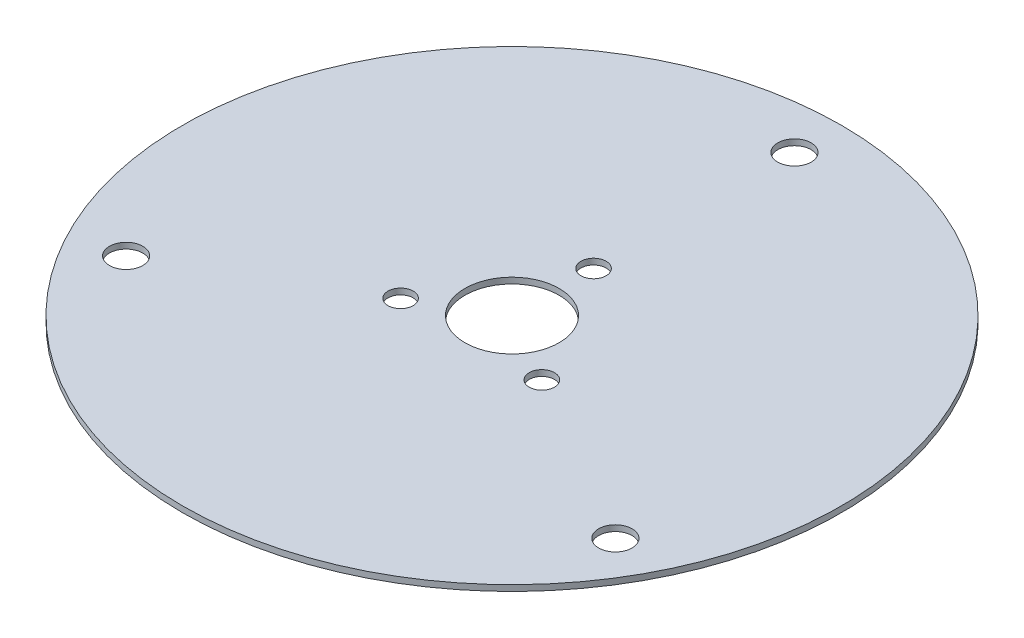
SolidWorks part; units mm, degrees
ref_plane "Front Plane" through (0, 0, 0) normal (0, 0, 1) x (1, 0, 0)
ref_plane "Top Plane" through (0, 0, 0) normal (0, 1, 0) x (1, 0, 0)
ref_plane "Right Plane" through (0, 0, 0) normal (1, 0, 0) x (0, 0, -1)
sketch "Sketch1" plane through (0, 0, 0) normal (0, 1, 0) x (1, 0, 0)
  circle A1 centre (0, 0) radius 44.45
  dimension "D2" = 88.9
extrude "Boss-Extrude1" add sketch "Sketch1" along normal blind 0.8
sketch "Sketch2" plane through (0, 0, 0) normal (0, 0, 1) x (1, 0, 0)
  line L0 (0, 6.2846) -> (0, -3.885) construction
sketch "Sketch7" plane through (0, 0.8, 0) normal (0, 1, 0) x (1, 0, 0)
  line L0 (0, 0) -> (0, 38.1) construction
  line L1 (0, 0) -> (32.9956, -19.05) construction
  line L2 (0, 0) -> (-32.9956, -19.05) construction
  point P10 (0, 0)
  dimension "D2" = 38.1
  dimension "D3" = 3
hole_wizard "M4 Clearance Hole1" positions "Sketch9" profile "Sketch8" hole size "M4" standard "ANSI Metric" end condition through all
sketch "Sketch9" plane through (0, 0.8, 0) normal (0, 1, 0) x (1, 0, 0)
  point P0 (0, 38.1)
  point P3 (-32.9956, -19.05)
  point P6 (32.9956, -19.05)
sketch "Sketch8" plane through (0, 0.8, -38.1) normal (1, 0, 0) x (0, 0, 1)
  line L0 (0, 0) -> (0, 0.8)
  line L1 (0, 0.8) -> (2.25, 0.8)
  line L2 (2.25, 0.8) -> (2.25, 0)
  line L5 (2.25, 0) -> (0, 0)
  line L11 (0, -6.35) -> (0, 107.95) construction
  dimension "Thru Hole Dia." = 4.5
  dimension "Thru Hole Depth" = 0.8
sketch "Sketch10" plane through (0, 0.8, 0) normal (0, 1, 0) x (1, 0, 0)
  line L0 (0, 0) -> (-38.4948, 22.225) construction
  line L1 (0, 0) -> (0, -44.45) construction
  line L2 (0, 0) -> (38.4948, 22.225) construction
  circle A0 centre (0, 0) radius 44.45 construction
  dimension "D1" = 120
  dimension "D2" = 120
sketch "Sketch11" plane through (0, 0.8, 0) normal (0, 1, 0) x (1, 0, 0)
  circle A6 centre (0, 0) radius 6.35
  dimension "D4" = 12.7
extrude "Cut-Extrude1" cut sketch "Sketch11" against normal through all
sketch "Sketch12" plane through (0, 0.8, 0) normal (0, 1, 0) x (1, 0, 0)
  line L0 (-9.5263, -5.5) -> (0, 0) construction
  line L1 (0, 0) -> (0, 11) construction
  line L2 (0, 11) -> (9.5263, -5.5) construction
  line L3 (9.5263, -5.5) -> (0, 0) construction
  line L4 (0, 11) -> (-9.5263, -5.5) construction
  line L5 (-9.5263, -5.5) -> (9.5263, -5.5) construction
  point P0 (0, 11)
  point P1 (-9.5263, -5.5)
  point P2 (9.5263, -5.5)
  dimension "D1" = 11
hole_wizard "M3 Clearance Hole1" positions "Sketch14" profile "Sketch13" hole size "M3" standard "ANSI Metric" end condition through all
sketch "Sketch14" plane through (0, 0.8, 0) normal (0, 1, 0) x (1, 0, 0)
  point P0 (0, 11)
  point P3 (-9.5263, -5.5)
  point P6 (9.5263, -5.5)
sketch "Sketch13" plane through (0, 0.8, -11) normal (1, 0, 0) x (0, 0, 1)
  line L0 (0, 0) -> (0, 0.8)
  line L1 (0, 0.8) -> (1.7, 0.8)
  line L2 (1.7, 0.8) -> (1.7, 0)
  line L5 (1.7, 0) -> (0, 0)
  line L11 (0, -6.35) -> (0, 107.95) construction
  dimension "Thru Hole Dia." = 3.4
  dimension "Thru Hole Depth" = 0.8
sketch "Sketch15" plane through (0, 0.8, 0) normal (0, 1, 0) x (1, 0, 0)
  circle A0 centre (0, 0) radius 11 construction
  circle A1 centre (0, 0) radius 38.1 construction
  circle A2 centre (0, 38.1) radius 2.25
  circle A3 centre (0, 11) radius 1.7
  circle A4 centre (0, 0) radius 6.35
  circle A7 centre (0, 0) radius 6.35 construction
  circle A8 centre (0, 11) radius 1.7 construction
  circle A9 centre (0, 38.1) radius 2.25 construction
